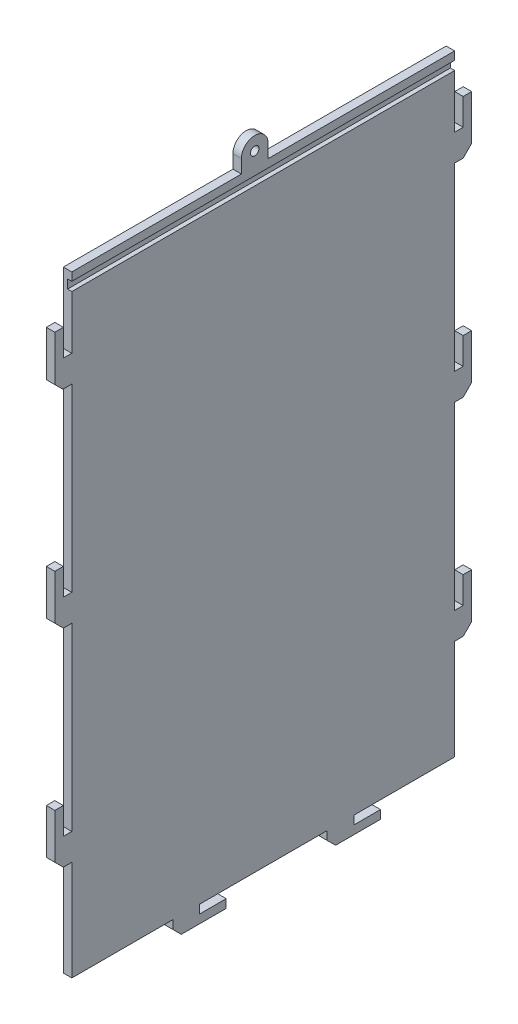
SolidWorks part; units mm, degrees
ref_plane "Front Plane" through (0, 0, 0) normal (0, 0, 1) x (1, 0, 0)
ref_plane "Top Plane" through (0, 0, 0) normal (0, 1, 0) x (1, 0, 0)
ref_plane "Right Plane" through (0, 0, 0) normal (1, 0, 0) x (0, 0, -1)
sketch "Sketch2" plane through (0, 0, 0) normal (1, 0, 0) x (0, 0, -1)
  line L3 (12.0032, 442.0977) -> (138.9532, 442.0977)
  line L4 (311.3032, 375.7477) -> (311.3032, 409.3977)
  line L8 (12.0032, -15.6023) -> (12.0032, 59.3977)
  line L12 (298.6032, -15.6023) -> (298.6032, 59.3977)
  line L17 (12.0032, -15.6023) -> (87.6032, -15.6023)
  line L20 (298.6032, 234.3977) -> (298.6032, 369.3977)
  line L21 (298.6032, 389.3977) -> (304.9532, 389.3977)
  line L22 (304.9532, 389.3977) -> (304.9532, 409.3977)
  line L23 (304.9532, 409.3977) -> (311.3032, 409.3977)
  line L24 (304.9532, 369.3977) -> (298.6032, 369.3977)
  line L25 (304.9532, 214.3977) -> (298.6032, 214.3977)
  line L26 (298.6032, 234.3977) -> (304.9532, 234.3977)
  line L27 (311.3032, 220.7477) -> (311.3032, 254.3977)
  line L28 (304.9532, 234.3977) -> (304.9532, 254.3977)
  line L29 (304.9532, 254.3977) -> (311.3032, 254.3977)
  line L30 (304.9532, 59.3977) -> (298.6032, 59.3977)
  line L31 (298.6032, 79.3977) -> (304.9532, 79.3977)
  line L32 (311.3032, 65.7477) -> (311.3032, 99.3977)
  line L33 (304.9532, 79.3977) -> (304.9532, 99.3977)
  line L34 (304.9532, 99.3977) -> (311.3032, 99.3977)
  line L35 (298.6032, 389.3977) -> (298.6032, 442.0977)
  line L36 (298.6032, 79.3977) -> (298.6032, 214.3977)
  line L37 (12.0032, 214.3661) -> (12.0032, 214.3977)
  line L38 (311.3032, 375.7477) -> (304.9532, 369.3977)
  line L39 (5.6532, 59.3977) -> (12.0032, 59.3977)
  line L40 (-0.6968, 65.7477) -> (-0.6968, 99.3977)
  line L41 (5.6532, 99.3977) -> (-0.6968, 99.3977)
  line L42 (5.6532, 79.3977) -> (5.6532, 99.3977)
  line L43 (12.0032, 79.3977) -> (5.6532, 79.3977)
  line L44 (5.6532, 214.3977) -> (12.0032, 214.3977)
  line L45 (-0.6968, 220.7477) -> (-0.6968, 254.3977)
  line L46 (5.6532, 254.3977) -> (-0.6968, 254.3977)
  line L47 (5.6532, 234.3977) -> (5.6532, 254.3977)
  line L48 (12.0032, 234.3977) -> (5.6532, 234.3977)
  line L49 (5.3132, 369.3977) -> (12.0032, 369.3977)
  line L50 (-0.6968, 375.4078) -> (-0.6968, 409.3977)
  line L51 (5.6532, 409.3977) -> (-0.6968, 409.3977)
  line L52 (5.6532, 389.3977) -> (5.6532, 409.3977)
  line L53 (12.0032, 389.3977) -> (5.6532, 389.3977)
  line L54 (12.0032, 389.3977) -> (12.0032, 442.0977)
  line L55 (12.0032, 234.3977) -> (12.0032, 369.3977)
  line L56 (12.0032, 79.3977) -> (12.0032, 214.3661)
  line L57 (311.3032, 220.7477) -> (304.9532, 214.3977)
  line L58 (311.3032, 65.7477) -> (304.9532, 59.3977)
  line L59 (5.6532, 59.3977) -> (-0.6968, 65.7477)
  line L60 (5.6532, 214.3977) -> (-0.6968, 220.7477)
  line L61 (5.3132, 369.3977) -> (-0.6968, 375.4078)
  line L62 (223.1032, -21.9523) -> (243.1032, -21.9523)
  line L63 (203.1032, -21.9523) -> (203.1032, -15.6023)
  line L64 (209.4532, -28.3023) -> (203.1032, -21.9523)
  line L65 (223.1032, -15.6023) -> (223.1032, -21.9523)
  line L66 (209.4532, -28.3023) -> (243.1032, -28.3023)
  line L67 (243.1032, -21.9523) -> (243.1032, -28.3023)
  line L68 (87.6032, -21.9523) -> (87.6032, -15.6023)
  line L69 (93.9532, -28.3023) -> (87.6032, -21.9523)
  line L70 (93.9532, -28.3023) -> (127.6032, -28.3023)
  line L71 (127.6032, -21.9523) -> (127.6032, -28.3023)
  line L72 (107.6032, -21.9523) -> (127.6032, -21.9523)
  line L73 (107.6032, -15.6023) -> (107.6032, -21.9523)
  line L74 (223.1032, -15.6023) -> (298.6032, -15.6023)
  line L75 (107.6032, -15.6023) -> (203.1032, -15.6023)
  line L76 (158.9532, 452.0977) -> (158.9532, 442.0977)
  line L77 (138.9532, 452.0977) -> (138.9532, 442.0977)
  line L78 (158.9532, 442.0977) -> (298.6032, 442.0977)
  arc A0 (158.9532, 452.0977) -> (138.9532, 452.0977) centre (148.9532, 452.0977) ccw
  circle A1 centre (148.9532, 452.0977) radius 3.175
  point P2 (2.4782, 99.3977)
  point P19 (8.8282, 59.3977)
  dimension "D41" = 20
  dimension "D42" = 126.95
  dimension "D2" = 6.35
  dimension "D3" = 6.35
  dimension "D4" = 6.35
  dimension "D5" = 6.35
  dimension "D6" = 3
  dimension "D7" = 286.6
  dimension "D8" = 40
  dimension "D9" = 6.35
  dimension "D10" = 40
  dimension "D11" = 20
  dimension "D12" = 6.35
  dimension "D13" = 6.35
  dimension "D14" = 6.35
  dimension "D15" = 6.35
  dimension "D16" = 6.35
  dimension "D17" = 6.35
  dimension "D18" = 6.35
  dimension "D19" = 20
  dimension "D20" = 40
  dimension "D21" = 20
  dimension "D22" = 20
  dimension "D23" = 40
  dimension "D24" = 6.35
  dimension "D25" = 6.35
  dimension "D26" = 6.35
  dimension "D27" = 6.35
  dimension "D28" = 6.35
  dimension "D29" = 155
  dimension "D30" = 155
  dimension "D31" = 52.7
  dimension "D32" = 52.7
  dimension "D33" = 457.7
  dimension "D34" = 155
  dimension "D35" = 2
  dimension "D36" = 95.5
  dimension "D37" = 95.5
  dimension "D38" = 6.35
  dimension "D39" = 6.35
  dimension "D40" = 6.35
extrude "Boss-Extrude1" add sketch "Sketch2" along normal blind 6.35
sketch "Sketch3" plane through (0, 0, -12.0032) normal (0, 0, 1) x (1, 0, 0)
  line L0 (6.35, 442.0977) -> (6.35, 389.3977) construction
  line L1 (6.35, 436.0017) -> (3.175, 436.0017)
  line L2 (6.35, 436.0017) -> (6.35, 429.3977)
  line L3 (6.35, 429.3977) -> (3.175, 429.3977)
  line L4 (3.175, 436.0017) -> (3.175, 429.3977)
  line L5 (6.35, 442.0977) -> (0, 442.0977) construction
  dimension "D1" = 6.096
  dimension "D2" = 6.604
  dimension "D3" = 3.175
extrude "Cut-Extrude1" cut sketch "Sketch3" against normal through all
